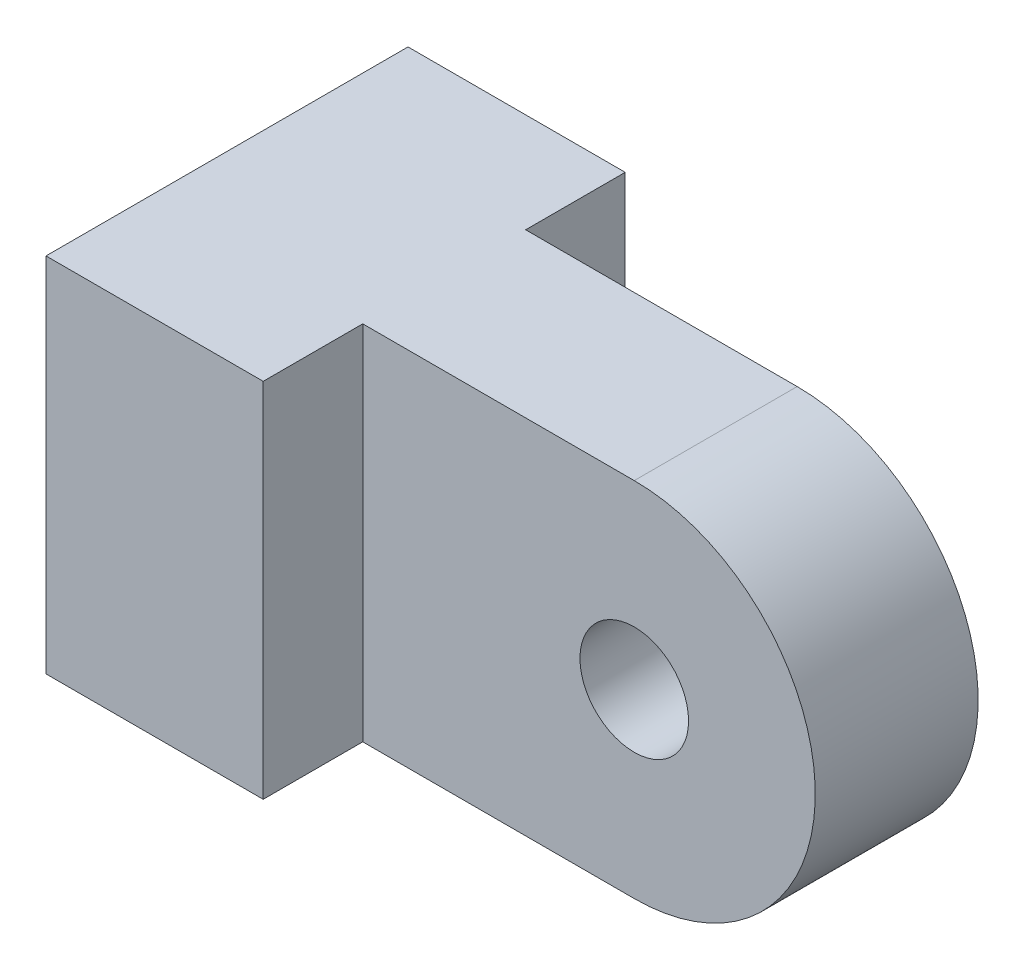
SolidWorks part; units mm, degrees
ref_plane "前视基准面" through (0, 0, 0) normal (0, 0, 1) x (1, 0, 0)
ref_plane "上视基准面" through (0, 0, 0) normal (0, 1, 0) x (1, 0, 0)
ref_plane "右视基准面" through (0, 0, 0) normal (1, 0, 0) x (0, 0, -1)
sketch "草图1" plane through (0, 0, 0) normal (1, 0, 0) x (0, 0, -1)
  line L1 (-10, -10) -> (10, -10)
  line L2 (-10, -10) -> (-10, 10)
  line L3 (-10, 10) -> (10, 10)
  line L4 (10, -10) -> (10, 10)
  line L5 (-10, -10) -> (10, 10) construction
  line L6 (-10, 10) -> (10, -10) construction
  circle A0 centre (0, 0) radius 7.5
  dimension "D2" = 15
  dimension "D3" = 20
extrude "凸台-拉伸1" add sketch "草图1" along normal blind 10
sketch "草图2" plane through (10, 0, 0) normal (1, 0, 0) x (0, 0, -1)
  line L0 (-10, 10) -> (-15, 10)
  line L1 (-15, 10) -> (-15, 8)
  line L2 (-15, 8) -> (-10, 8)
  line L3 (-10, 10) -> (-10, -10) construction
  line L4 (-10, 8) -> (-10, 10)
  line L6 (-10, -10) -> (-15, -10)
  line L7 (-15, -10) -> (-15, -8)
  line L8 (-15, -8) -> (-10, -8)
  line L9 (-10, -8) -> (-10, -10)
  line L14 (10, -10) -> (15, -10)
  line L15 (15, -10) -> (15, -8)
  line L16 (15, -8) -> (10, -8)
  line L17 (10, -8) -> (10, -10)
  line L26 (10, 10) -> (15, 10)
  line L27 (15, 8) -> (10, 8)
  line L28 (10, 8) -> (10, 10)
  line L29 (15, 10) -> (15, 8)
  line L34 (10, 10) -> (10, 15) [skipped]
  line L35 (8, 15) -> (8, 10) [skipped]
  line L36 (10, 15) -> (8, 15) [skipped]
  line L37 (8, 10) -> (10, 10) [skipped]
  line L38 (8, -10) -> (10, -10) [skipped]
  line L39 (10, -10) -> (10, -15) [skipped]
  line L40 (8, -15) -> (8, -10) [skipped]
  line L41 (10, -15) -> (8, -15) [skipped]
  line L42 (-10, -10) -> (-10, -15) [skipped]
  line L43 (-10, -15) -> (-8, -15) [skipped]
  line L44 (-8, -15) -> (-8, -10) [skipped]
  line L45 (-8, -10) -> (-10, -10) [skipped]
  line L46 (-10, 15) -> (-8, 15) [skipped]
  line L47 (-8, 15) -> (-8, 10) [skipped]
  line L48 (-10, 10) -> (-10, 15) [skipped]
  line L49 (-8, 10) -> (-10, 10) [skipped]
  point P28 (0, 0)
  point P41 (0, 0)
  dimension "D1" = 5
  dimension "D2" = 2
  dimension "D3" = 2
  dimension "D4" = 4
  dimension "D5" = 4
extrude "凸台-拉伸2" add sketch "草图2" along normal blind 0.0001 and the other way blind 10
sketch "草图3" plane through (0, 10, 0) normal (0, 1, 0) x (1, 0, 0)
  line L1 (0, 10) -> (10.0001, 15) construction
  circle A0 centre (5, 12.5) radius 1.5
  circle A1 centre (5.0001, -12.5) radius 1.5
  dimension "D1" = 2
extrude "切除-拉伸1" cut sketch "草图3" against normal through all
sketch "草图4" plane through (10, 0, 0) normal (1, 0, 0) x (0, 0, -1)
  line L1 (-10, 10) -> (10, 10)
  line L2 (-10, 10) -> (-10, -10)
  line L3 (-10, -10) -> (10, -10)
  line L4 (10, 10) -> (10, -10)
extrude "凸台-拉伸3" add sketch "草图4" along normal blind 2
sketch "草图5" plane through (12, 0, 0) normal (1, 0, 0) x (0, 0, -1)
  line L2 (4.5, -10) -> (-4.5, -10)
  line L3 (4.5, -10) -> (4.5, 10)
  line L4 (4.5, 10) -> (-4.5, 10)
  line L5 (-4.5, -10) -> (-4.5, 10)
  line L6 (4.5, -10) -> (-4.5, 10) construction
  line L7 (4.5, 10) -> (-4.5, -10) construction
  point P4 (0, 0)
  dimension "D1" = 9
extrude "凸台-拉伸4" add sketch "草图5" along normal blind 25 contours L5 L4 L3 L2
sketch "草图7" plane through (0, 0, -4.5) normal (0, 0, -1) x (-1, 0, 0)
  line L0 (-37, 0) -> (-30, 0)
  line L1 (-37, -10) -> (-37, 10) construction
  line L2 (-30, 0) -> (-27, 0)
  circle A0 centre (-27, 0) radius 3
  dimension "D1" = 7
  dimension "D2" = 3
extrude "切除-拉伸2" cut sketch "草图7" against normal blind 10
sketch "草图8" plane through (0, 0, -4.5) normal (0, 0, -1) x (-1, 0, 0)
  line L0 (-37, -10) -> (-12, -10) construction
  line L1 (-37, 10) -> (-12, 10) construction
  line L2 (-27, -10) -> (-37, -10)
  line L3 (-37, -10) -> (-37, 10)
  line L4 (-37, -10) -> (-37, 10) construction
  line L5 (-37, 10) -> (-27, 10)
  arc A0 (-27, -10) -> (-27, 10) centre (-27, 0) cw
  line M3 (-12, 10) -> (-37, 10)
  line M4 (-37, 10) -> (-37, -10)
  line M5 (-37, -10) -> (-12, -10)
extrude "切除-拉伸3" cut sketch "草图8" against normal blind 10 contours A0 L3 M5 | A0 M4 M3
sketch "草图9" plane through (0, -10, 0) normal (0, -1, 0) x (1, 0, 0)
  line L1 (0, -15) -> (10.0001, -15)
  line L2 (0, -15) -> (0, -10)
  line L3 (0, -10) -> (10.0001, -10)
  line L4 (10.0001, -15) -> (10.0001, -10)
  line L5 (0, 15) -> (10.0001, 15)
  line L6 (0, 15) -> (0, 10)
  line L7 (0, 10) -> (10.0001, 10)
  line L8 (10.0001, 15) -> (10.0001, 10)
extrude "切除-拉伸4" cut sketch "草图9" against normal through all
